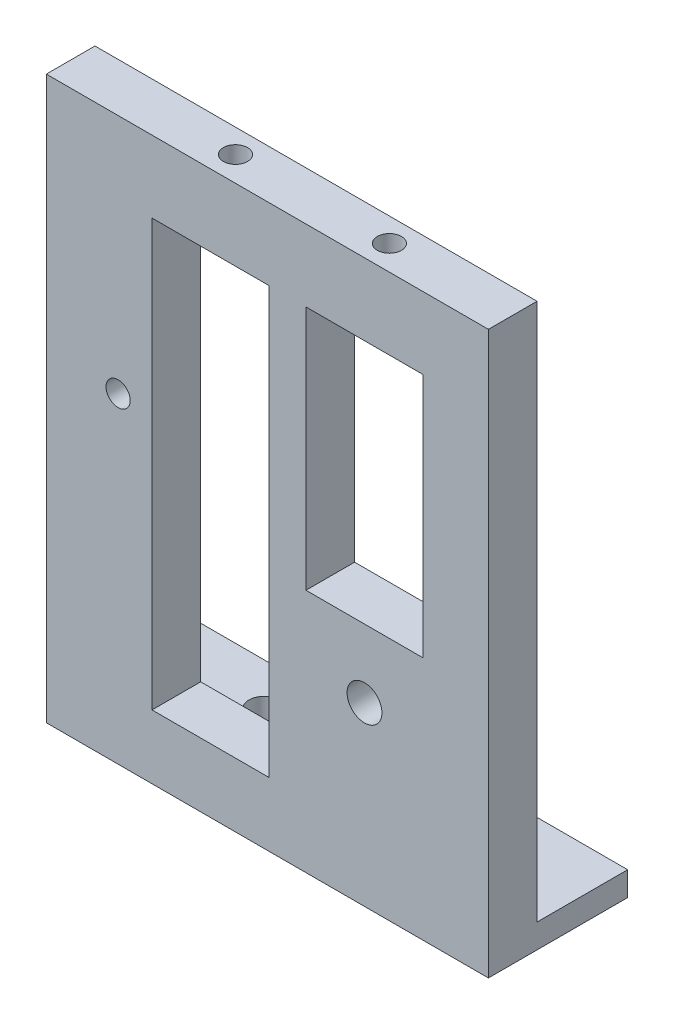
SolidWorks part; units mm, degrees
ref_plane "前视基准面" through (0, 0, 0) normal (0, 0, 1) x (1, 0, 0)
ref_plane "上视基准面" through (0, 0, 0) normal (0, 1, 0) x (1, 0, 0)
ref_plane "右视基准面" through (0, 0, 0) normal (1, 0, 0) x (0, 0, -1)
other "Configuration Table"
sketch "草图1" plane through (0, 0, -616.8369) normal (0, 0, 1) x (1, 0, 0)
  line L1 (-666.6246, 1338.1785) -> (-300.6946, 1338.1785)
  line L2 (-666.6246, 1338.1785) -> (-666.6246, 883.1785)
  line L3 (-666.6246, 883.1785) -> (-300.6946, 883.1785)
  line L4 (-300.6946, 1338.1785) -> (-300.6946, 883.1785)
  line L5 (-579.1312, 1278.7166) -> (-482.2212, 1278.7166)
  line L6 (-579.1312, 1278.7166) -> (-579.1312, 926.1266)
  line L7 (-579.1312, 926.1266) -> (-482.2212, 926.1266)
  line L8 (-482.2212, 1278.7166) -> (-482.2212, 926.1266)
  line L9 (-451.7196, 1278.7166) -> (-354.8096, 1278.7166)
  line L10 (-451.7196, 1278.7166) -> (-451.7196, 1075.6206)
  line L11 (-451.7196, 1075.6206) -> (-354.8096, 1075.6206)
  line L12 (-354.8096, 1278.7166) -> (-354.8096, 1075.6206)
  circle A0 centre (-607.2108, 1138.805) radius 10
  circle A1 centre (-403.2646, 1019.1785) radius 14.4381
extrude "凸台-拉伸1" add sketch "草图1" against normal up to surface (40.26 mm away)
sketch "草图2" plane through (0, 1338.1785, 0) normal (0, 1, 0) x (1, 0, 0)
  circle A0 centre (-530.6762, 637.4469) radius 10
  circle A1 centre (-403.2646, 637.4469) radius 10
extrude "切除-拉伸1" cut sketch "草图2" against normal up to next and the other way through all
sketch "草图3" plane through (0, 0, -657.0969) normal (0, 0, -1) x (-1, 0, 0)
  line L0 (666.6246, 883.1785) -> (666.6246, 1338.1785) construction
  line L1 (300.6946, 883.1785) -> (666.6246, 883.1785)
  line L2 (300.6946, 883.1785) -> (300.6946, 903.1785)
  line L3 (300.6946, 903.1785) -> (666.6246, 903.1785)
  line L4 (666.6246, 883.1785) -> (666.6246, 903.1785)
  dimension "D1" = 20
extrude "凸台-拉伸2" add sketch "草图3" along normal blind 80
ref_plane "基准面1" through (-320.6946, 0, 0) normal (1, 0, 0) x (0, 0, -1)
sketch "草图4" plane through (-320.6946, 0, 0) normal (1, 0, 0) x (0, 0, -1)
  line L0 (657.0969, 993.1785) -> (707.0969, 903.1785)
  line L1 (657.0969, 1338.1785) -> (657.0969, 903.1785) construction
  line L2 (737.0969, 903.1785) -> (657.0969, 903.1785) construction
  dimension "D1" = 50
  dimension "D2" = 90
ref_plane "基准面2" through (-646.6246, 0, 0) normal (-1, 0, 0) x (0, 0, 1)
sketch "草图6" plane through (0, 903.1785, 0) normal (0, 1, 0) x (1, 0, 0)
  line L0 (-666.6246, 697.0969) -> (-300.6946, 697.0969) construction
  line L1 (-666.6246, 737.0969) -> (-666.6246, 657.0969) construction
  line L2 (-300.6946, 737.0969) -> (-300.6946, 657.0969) construction
  circle A0 centre (-566.6246, 697.0969) radius 12.5
  circle A1 centre (-400.6946, 697.0969) radius 12.5
  dimension "D1" = 25
  dimension "D2" = 25
  dimension "D3" = 100
  dimension "D4" = 100
extrude "切除-拉伸2" cut sketch "草图6" against normal up to next
sketch "草图9" plane through (-300.6946, 0, 0) normal (1, 0, 0) x (0, 0, -1)
  line L0 (737.0969, 903.1785) -> (657.0969, 903.1785) construction
  line L1 (737.0969, 883.1785) -> (732.0969, 883.1785)
  line L2 (737.0969, 883.1785) -> (737.0969, 903.1785)
  line L3 (737.0969, 903.1785) -> (732.0969, 903.1785)
  line L4 (732.0969, 883.1785) -> (732.0969, 903.1785)
  dimension "D1" = 5
extrude "切除-拉伸4" cut sketch "草图9" against normal through all both and the other way through all
sketch "草图10" plane through (-300.6946, 0, 0) normal (1, 0, 0) x (0, 0, -1)
  line L0 (732.0969, 903.1785) -> (732.0969, 883.1785)
  line L2 (732.0969, 893.1785) -> (657.0969, 893.1785)
  line L3 (732.0969, 893.1785) -> (732.0969, 903.1785)
  line L4 (732.0969, 903.1785) -> (657.0969, 903.1785)
  line L5 (657.0969, 893.1785) -> (657.0969, 903.1785)
  line M6 (732.0969, 903.1785) -> (657.0969, 903.1785)
extrude "切除-拉伸5" cut sketch "草图10" against normal through all both and the other way through all contours L5 L2 L0 M6
sketch "草图11" plane through (0, 883.1785, 0) normal (0, -1, 0) x (1, 0, 0)
  line L1 (-666.6246, -616.8369) -> (-300.6946, -616.8369)
  line L2 (-666.6246, -616.8369) -> (-666.6246, -732.0969)
  line L3 (-666.6246, -732.0969) -> (-300.6946, -732.0969)
  line L4 (-300.6946, -616.8369) -> (-300.6946, -732.0969)
  circle A0 centre (-400.6946, -697.0969) radius 12.5
  circle A1 centre (-566.6246, -697.0969) radius 12.5
extrude "凸台-拉伸4" add sketch "草图11" along normal up to surface (10 mm away)
